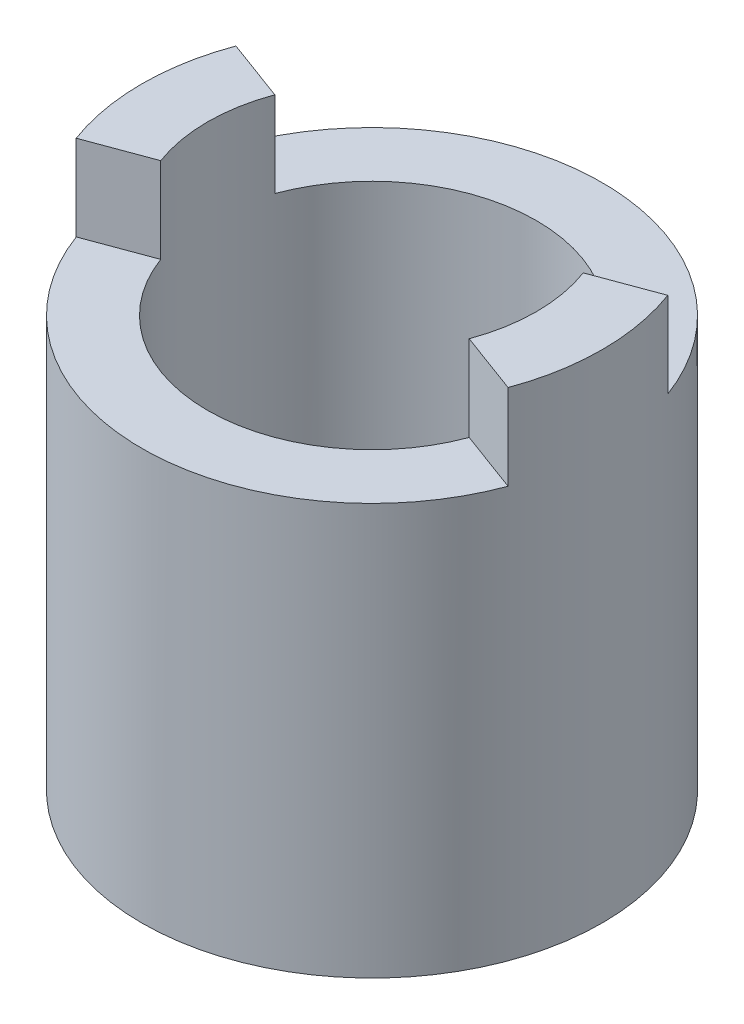
SolidWorks part; units mm, degrees
ref_plane "Front Plane" through (0, 0, 0) normal (0, 0, 1) x (1, 0, 0)
ref_plane "Top Plane" through (0, 0, 0) normal (0, 1, 0) x (1, 0, 0)
ref_plane "Right Plane" through (0, 0, 0) normal (1, 0, 0) x (0, 0, -1)
sketch "Sketch1" plane through (0, 0, 0) normal (0, 1, 0) x (1, 0, 0)
  circle A0 centre (0, 0) radius 2.5
  circle A1 centre (0, 0) radius 3.5
extrude "Boss-Extrude1" add sketch "Sketch1" along normal blind 6.25
sketch "Sketch2" plane through (0, 6.25, 0) normal (0, 1, 0) x (1, 0, 0)
  line L0 (2.3448, 0.8672) -> (3.2827, 1.2141)
  line L1 (0, 0) -> (3.5, 0) construction
  line L2 (2.3448, -0.8672) -> (3.2827, -1.2141)
  line L3 (0, 0) -> (0, 3.5) construction
  line L4 (-2.3448, -0.8672) -> (-3.2827, -1.2141)
  line L5 (-2.3448, 0.8672) -> (-3.2827, 1.2141)
  arc A0 (-3.2827, 1.2141) -> (-3.2827, -1.2141) centre (0, 0) ccw
  arc A1 (-2.3448, 0.8672) -> (-2.3448, -0.8672) centre (0, 0) ccw
  arc A2 (2.3448, -0.8672) -> (2.3448, 0.8672) centre (0, 0) ccw
  arc A3 (3.2827, -1.2141) -> (3.2827, 1.2141) centre (0, 0) ccw
extrude "Boss-Extrude2" add sketch "Sketch2" along normal blind 1.3
